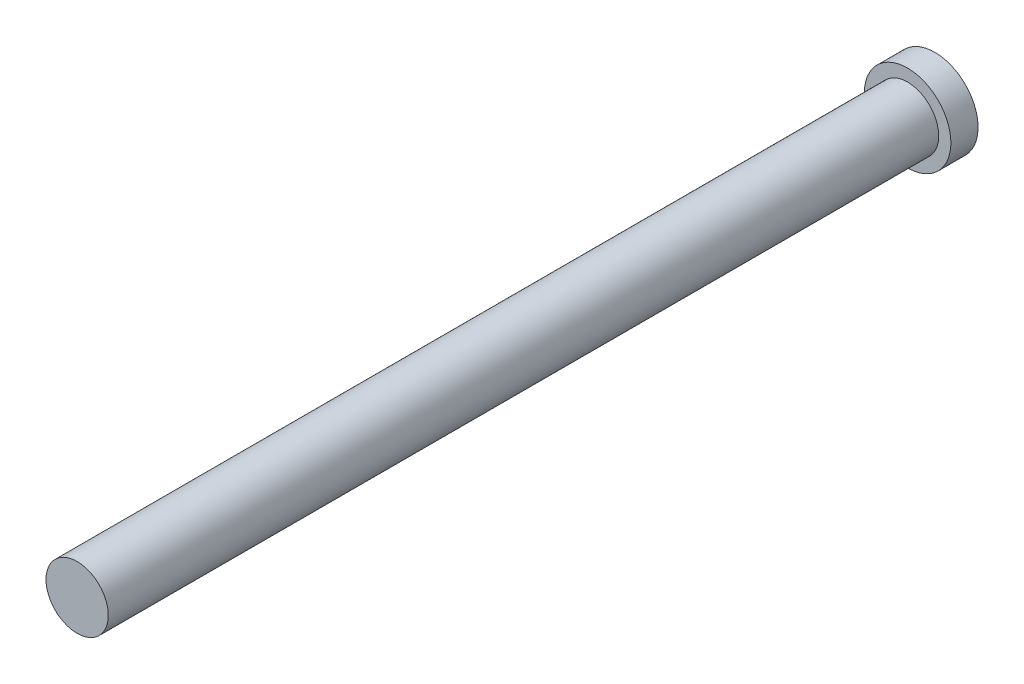
SolidWorks part; units mm, degrees
material "Cast Stainless Steel"
ref_plane "Front Plane" through (0, 0, 0) normal (0, 0, 1) x (1, 0, 0)
ref_plane "Top Plane" through (0, 0, 0) normal (0, 1, 0) x (1, 0, 0)
ref_plane "Right Plane" through (0, 0, 0) normal (1, 0, 0) x (0, 0, -1)
sketch "Sketch1" plane through (0, 0, 0) normal (0, 0, 1) x (1, 0, 0)
  circle A0 centre (0, 0) radius 1.143
  dimension "D1" = 2.286
extrude "Boss-Extrude1" add sketch "Sketch1" along normal blind 30.48
sketch "Sketch2" plane through (0, 0, 0) normal (0, 0, -1) x (-1, 0, 0)
  circle A0 centre (0, 0) radius 1.5875
  dimension "D1" = 3.175
extrude "Boss-Extrude2" add sketch "Sketch2" along normal blind 1
